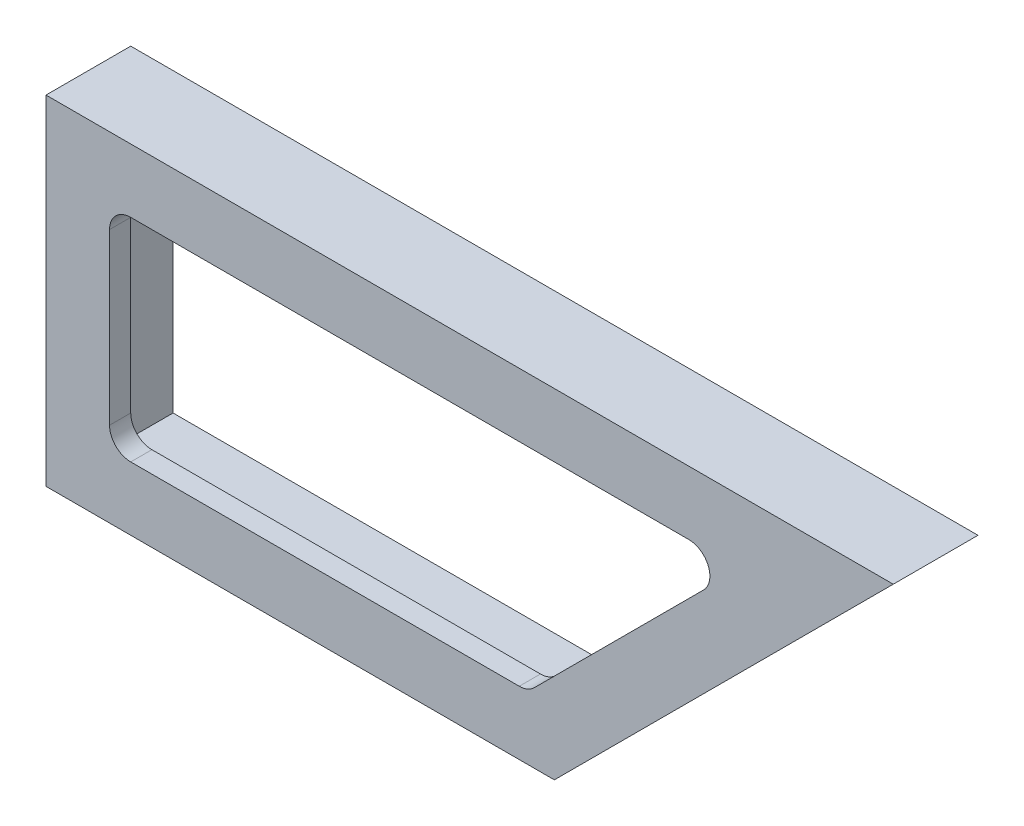
SolidWorks part; units mm, degrees
ref_plane "Front Plane" through (0, 0, 0) normal (0, 0, 1) x (1, 0, 0)
ref_plane "Top Plane" through (0, 0, 0) normal (0, 1, 0) x (1, 0, 0)
ref_plane "Right Plane" through (0, 0, 0) normal (1, 0, 0) x (0, 0, -1)
sketch "Sketch1" plane through (0, 0, 0) normal (0, 0, 1) x (1, 0, 0)
  line L0 (0, 0) -> (8, 8)
  line L1 (0, 0) -> (-12, 0)
  line L3 (0, 8) -> (-12, 8)
  line L4 (-12, 0) -> (-12, 8)
  line L5 (8, 8) -> (0, 8)
  dimension "D1" = 12
  dimension "D2" = 8
  dimension "D3" = 8
extrude "Boss-Extrude1" add sketch "Sketch1" along normal blind 2
sketch "Sketch2" plane through (0, 0, 0) normal (0, 0, -1) x (-1, 0, 0)
  line L0 (0.4142, 7) -> (-5.5858, 7)
  line L1 (11, 7) -> (0.4142, 7)
  line L2 (11, 7) -> (11, 1)
  line L3 (11, 1) -> (0.4142, 1)
  line L5 (-5.5858, 7) -> (0.4142, 1)
  line L6 (-8, 8) -> (12, 8) construction
  line L7 (12, 8) -> (12, 0) construction
  line L8 (0, 0) -> (-8, 8) construction
  dimension "D1" = 6
  dimension "D2" = 1
  dimension "D3" = 1
  dimension "D4" = 6
  dimension "D5" = 1
extrude "Cut-Extrude1" cut sketch "Sketch2" against normal blind 1.5
sketch "Sketch3" plane through (0, 0, 2) normal (0, 0, 1) x (1, 0, 0)
  line L0 (0, 6.5) -> (4.3787, 6.5)
  line L1 (-10.5, 6.5) -> (0, 6.5)
  line L2 (-10.5, 6.5) -> (-10.5, 1.5)
  line L3 (-10.5, 1.5) -> (-0.6213, 1.5)
  line L4 (8, 8) -> (-12, 8) construction
  line L5 (4.3787, 6.5) -> (-0.6213, 1.5)
  line L6 (-12, 8) -> (-12, 0) construction
  line L7 (-12, 0) -> (0, 0) construction
  line L8 (0, 0) -> (8, 8) construction
  dimension "D1" = 1.5
  dimension "D2" = 1.5
  dimension "D3" = 1.5
  dimension "D4" = 1.5
  dimension "D5" = 1.5
extrude "Cut-Extrude2" cut sketch "Sketch3" against normal through all
fillet "Fillet1" radius 0.5 4 edges at (-0.6213, 1.5, 1.75) (4.3787, 6.5, 1.75) (-10.5, 1.5, 1.75) (-10.5, 6.5, 1.75)
